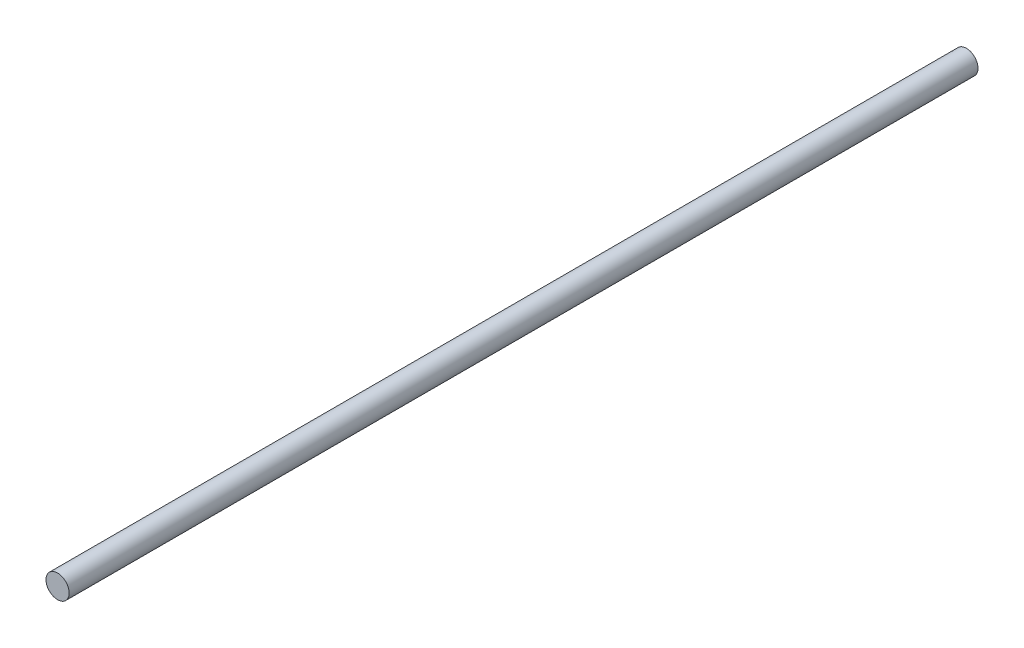
SolidWorks part; units mm, degrees
material "aplakash"
ref_plane "Front Plane" through (0, 0, 0) normal (0, 0, 1) x (1, 0, 0)
ref_plane "Top Plane" through (0, 0, 0) normal (0, 1, 0) x (1, 0, 0)
ref_plane "Right Plane" through (0, 0, 0) normal (1, 0, 0) x (0, 0, -1)
sketch "Sketch1" plane through (0, 0, 0) normal (0, 0, 1) x (1, 0, 0)
  circle A0 centre (0, 0) radius 2.5
  dimension "D1" = 5
extrude "Boss-Extrude1" add sketch "Sketch1" along normal mid plane 196
